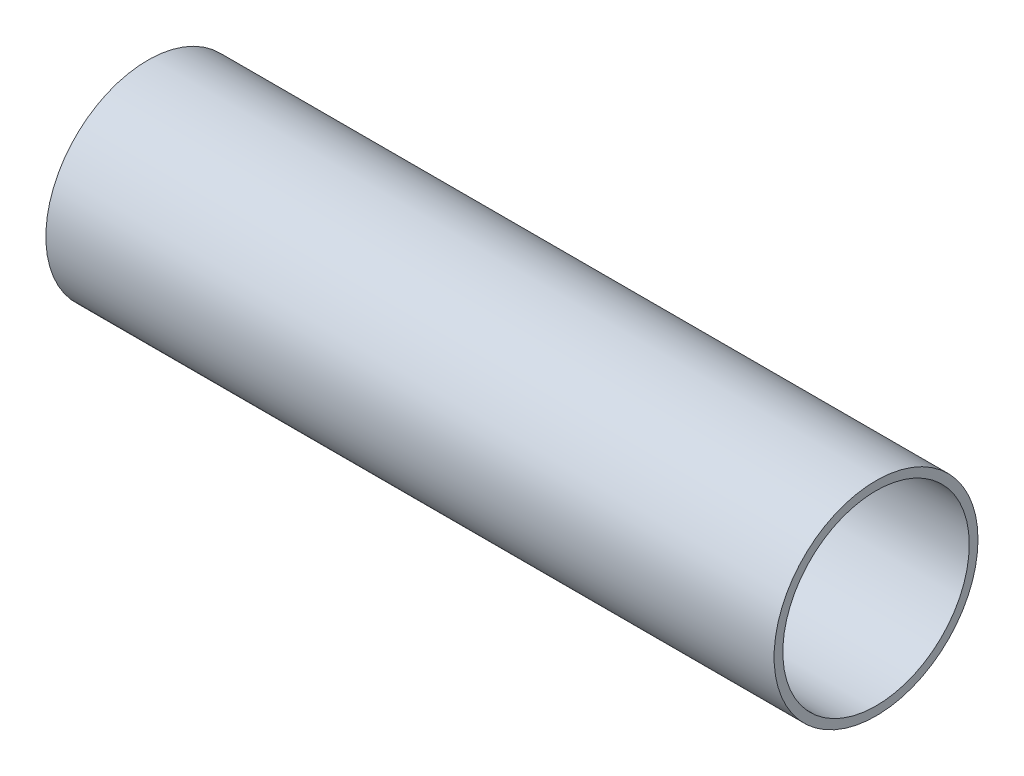
SolidWorks part; units mm, degrees
ref_plane "Front Plane" through (0, 0, 0) normal (0, 0, 1) x (1, 0, 0)
ref_plane "Top Plane" through (0, 0, 0) normal (0, 1, 0) x (1, 0, 0)
ref_plane "Right Plane" through (0, 0, 0) normal (1, 0, 0) x (0, 0, -1)
sketch "Sketch3" plane through (0, 0, 0) normal (1, 0, 0) x (0, 0, -1)
  circle A0 centre (0, 0) radius 32
  circle A1 centre (0, 0) radius 35
  dimension "D1" = 64
  dimension "D2" = 70
extrude "Boss-Extrude1" add sketch "Sketch3" along normal blind 250
